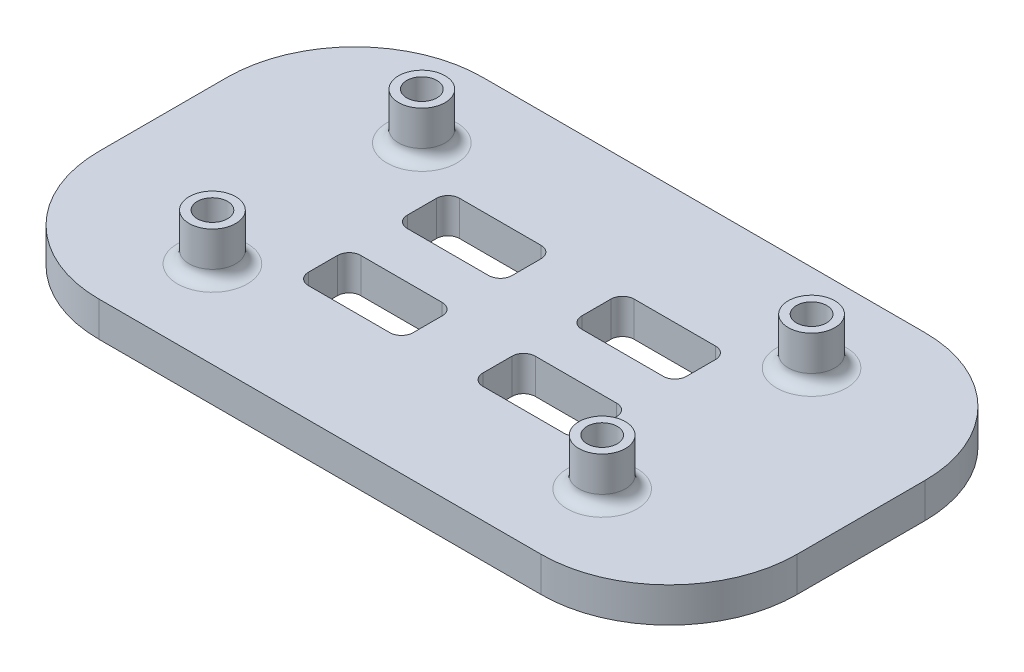
SolidWorks part; units mm, degrees
ref_plane "Front Plane" through (0, 0, 0) normal (0, 0, 1) x (1, 0, 0)
ref_plane "Top Plane" through (0, 0, 0) normal (0, 1, 0) x (1, 0, 0)
ref_plane "Right Plane" through (0, 0, 0) normal (1, 0, 0) x (0, 0, -1)
sketch "Sketch1" plane through (0, 0, 0) normal (0, 1, 0) x (1, 0, 0)
  line L0 (0, 0) -> (30, 0) construction
  line L1 (-30, 16.5) -> (30, 16.5)
  line L2 (-30, 16.5) -> (-30, -16.5)
  line L3 (-30, -16.5) -> (30, -16.5)
  line L4 (30, 16.5) -> (30, -16.5)
  line L5 (-25, 11.5) -> (25, 11.5) construction
  line L6 (-25, 11.5) -> (-25, -11.5) construction
  line L7 (-25, -11.5) -> (25, -11.5) construction
  line L8 (25, 11.5) -> (25, -11.5) construction
  line L9 (0, 0) -> (0, 16.5) construction
  dimension "D1" = 60
  dimension "D2" = 33
  dimension "D3" = 5
  dimension "D4" = 5
  dimension "D5" = 5
  dimension "D6" = 5
extrude "Boss-Extrude1" add sketch "Sketch1" along normal blind 3
sketch "Sketch2" plane through (0, 3, 0) normal (0, 1, 0) x (1, 0, 0)
  line L0 (0, 0) -> (0, 16.5) construction
  line L1 (0, 0) -> (30, 0) construction
  line L2 (0, 0) -> (0, -11.5) construction
  line L3 (-25, -11.5) -> (25, -11.5) construction
  circle A0 centre (-16.75, 9) radius 1.3
  circle A1 centre (16.75, 9) radius 1.3
  circle A2 centre (-16.75, -9) radius 1.3
  circle A3 centre (16.75, -9) radius 1.3
  dimension "D1" = 2.6
  dimension "D2" = 33.5
  dimension "D3" = 18
  dimension "D4" = 16.75
  dimension "D5" = 9
extrude "Cut-Extrude1" cut sketch "Sketch2" against normal blind 3
sketch "Sketch3" plane through (0, 3, 0) normal (0, 1, 0) x (1, 0, 0)
  circle A0 centre (-16.75, 9) radius 1.3
  circle A1 centre (-16.75, 9) radius 2
  circle A2 centre (-16.75, -9) radius 1.3
  circle A3 centre (-16.75, -9) radius 2
  circle A4 centre (16.75, -9) radius 1.3
  circle A5 centre (16.75, -9) radius 2
  circle A6 centre (16.75, 9) radius 1.3
  circle A7 centre (16.75, 9) radius 2
  circle A8 centre (16.75, 9) radius 1.3 construction
  dimension "D1" = 4
extrude "Boss-Extrude2" add sketch "Sketch3" along normal blind 4
fillet "Fillet1" radius 1 4 edges at (16.75, 3, -7) (16.75, 3, 11) (-16.75, 3, -7) (-16.75, 3, 11)
sketch "Sketch4" plane through (0, 0, 0) normal (0, -1, 0) x (1, 0, 0)
  line L0 (-25, 11.5) -> (25, 11.5) construction
  line L1 (-15.5087, 6.85) -> (-14.2674, 9)
  line L2 (-14.2674, 9) -> (-15.5087, 11.15)
  line L3 (-15.5087, 11.15) -> (-17.9913, 11.15)
  line L4 (-17.9913, 11.15) -> (-19.2326, 9)
  line L5 (-19.2326, 9) -> (-17.9913, 6.85)
  line L6 (-17.9913, 6.85) -> (-15.5087, 6.85)
  line L7 (0, 16.5) -> (0, -16.5) construction
  line L8 (-30, 16.5) -> (30, 16.5) construction
  line L9 (30, 0) -> (-30, 0) construction
  line L10 (-30, -16.5) -> (-30, 16.5) construction
  line L11 (17.9913, 6.85) -> (15.5087, 6.85)
  line L12 (19.2326, 9) -> (17.9913, 6.85)
  line L13 (17.9913, 11.15) -> (19.2326, 9)
  line L14 (15.5087, 11.15) -> (17.9913, 11.15)
  line L15 (14.2674, 9) -> (15.5087, 11.15)
  line L16 (15.5087, 6.85) -> (14.2674, 9)
  line L29 (15.5087, -6.85) -> (14.2674, -9)
  line L30 (14.2674, -9) -> (15.5087, -11.15)
  line L31 (15.5087, -11.15) -> (17.9913, -11.15)
  line L32 (17.9913, -11.15) -> (19.2326, -9)
  line L33 (19.2326, -9) -> (17.9913, -6.85)
  line L34 (17.9913, -6.85) -> (15.5087, -6.85)
  line L35 (-17.9913, -6.85) -> (-15.5087, -6.85)
  line L36 (-19.2326, -9) -> (-17.9913, -6.85)
  line L37 (-17.9913, -11.15) -> (-19.2326, -9)
  line L38 (-15.5087, -11.15) -> (-17.9913, -11.15)
  line L39 (-14.2674, -9) -> (-15.5087, -11.15)
  line L40 (-15.5087, -6.85) -> (-14.2674, -9)
  circle A0 centre (-16.75, 9) radius 2.15 construction
  circle A1 centre (16.75, 9) radius 2.15 construction
  circle A2 centre (-16.75, 9) radius 2.15 construction
  circle A3 centre (16.75, 9) radius 2.15 construction
  circle A4 centre (16.75, -9) radius 2.15 construction
  circle A5 centre (-16.75, -9) radius 2.15 construction
  circle A6 centre (16.75, -9) radius 2.15 construction
  circle A7 centre (-16.75, -9) radius 2.15 construction
  dimension "D1" = 4.3
extrude "Cut-Extrude2" cut sketch "Sketch4" against normal blind 2
fillet "Fillet2" radius 11 4 edges at (-30, 1.5, 16.5) (30, 1.5, 16.5) (30, 1.5, -16.5) (-30, 1.5, -16.5)
sketch "Sketch5" plane through (0, 3, 0) normal (0, 1, 0) x (1, 0, 0)
  line L0 (0, 0) -> (0, 16.5) construction
  line L1 (-12, 6.5) -> (-3, 6.5)
  line L2 (-12, 6.5) -> (-12, 2)
  line L3 (-12, 2) -> (-3, 2)
  line L4 (-3, 6.5) -> (-3, 2)
  line L5 (-25, 11.5) -> (25, 11.5) construction
  line L6 (-25, 11.5) -> (-25, -11.5) construction
  line L7 (0, 0) -> (30, 0) construction
  line L8 (0, 16.5) -> (0, -16.5) construction
  line L9 (-30, -16.5) -> (30, -16.5) construction
  line L10 (-30, 0) -> (30, 0) construction
  line L11 (-30, 16.5) -> (-30, -16.5) construction
  line L12 (3, 6.5) -> (3, 2)
  line L13 (12, 2) -> (3, 2)
  line L14 (12, 6.5) -> (12, 2)
  line L15 (12, 6.5) -> (3, 6.5)
  line L16 (12, -6.5) -> (3, -6.5)
  line L17 (12, -6.5) -> (12, -2)
  line L18 (12, -2) -> (3, -2)
  line L19 (3, -6.5) -> (3, -2)
  line L20 (-3, -6.5) -> (-3, -2)
  line L21 (-12, -2) -> (-3, -2)
  line L22 (-12, -6.5) -> (-12, -2)
  line L23 (-12, -6.5) -> (-3, -6.5)
  dimension "D1" = 3
  dimension "D2" = 5
  dimension "D3" = 13
  dimension "D4" = 2
extrude "Cut-Extrude3" cut sketch "Sketch5" against normal through all
fillet "Fillet3" radius 1 16 edges at (12, 1.5, -6.5) (3, 1.5, -6.5) (3, 1.5, -2) (12, 1.5, -2) (12, 1.5, 6.5) (12, 1.5, 2) (3, 1.5, 2) (3, 1.5, 6.5) (-12, 1.5, 6.5) (-3, 1.5, 6.5) (-3, 1.5, 2) (-12, 1.5, 2) (-12, 1.5, -2) (-12, 1.5, -6.5) (-3, 1.5, -6.5) (-3, 1.5, -2)
